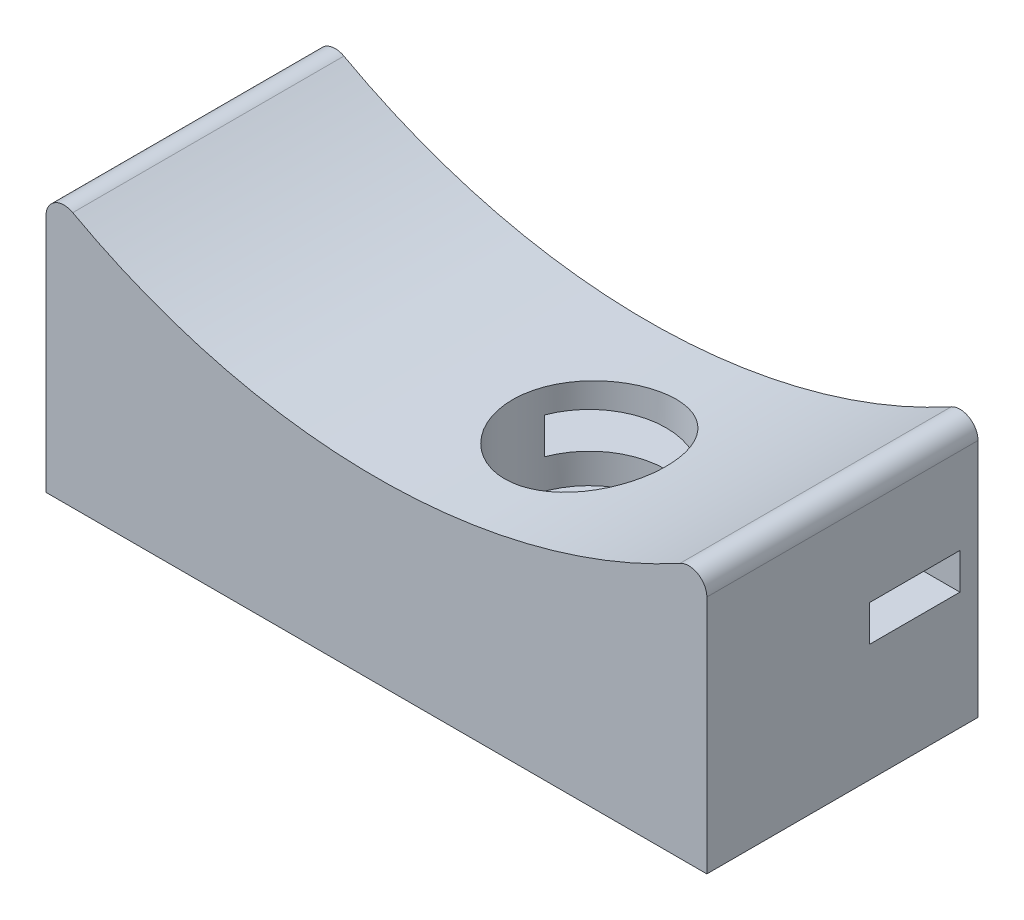
SolidWorks part; units mm, degrees
ref_plane "Front Plane" through (0, 0, 0) normal (0, 0, 1) x (1, 0, 0)
ref_plane "Top Plane" through (0, 0, 0) normal (0, 1, 0) x (1, 0, 0)
ref_plane "Right Plane" through (0, 0, 0) normal (1, 0, 0) x (0, 0, -1)
sketch "Sketch2" plane through (0, 0, 0) normal (0, 0, 1) x (1, 0, 0)
  line L0 (0, 15) -> (0, 0)
  line L1 (0, 0) -> (36.5591, 0)
  line L2 (36.5591, 0) -> (36.5591, 15)
  arc A0 (0, 15) -> (36.5591, 15) centre (18.2795, 44.8473) ccw
  dimension "D10" = 70
  dimension "D2" = 15
  dimension "D3" = 36.5591
extrude "Boss-Extrude2" add sketch "Sketch2" along normal blind 15
sketch "Sketch4" plane through (0, 0, 0) normal (0, -1, 0) x (1, 0, 0)
  line L0 (0, 15) -> (36.5591, 15) construction
  line L1 (36.5591, 15) -> (36.5591, 0) construction
  circle A0 centre (22.5591, 7.5) radius 2.5
  dimension "D3" = 5
  dimension "D1" = 7.5
  dimension "D2" = 14
extrude "Cut-Extrude1" cut sketch "Sketch4" against normal blind 15
ref_plane "Plane1" through (0, 9.8473, 0) normal (0, 1, 0) x (1, 0, 0)
sketch "Sketch5" plane through (0, 9.8473, 0) normal (0, 1, 0) x (1, 0, 0)
  circle A0 centre (22.5591, -7.5) radius 4.25
  dimension "D1" = 8.5
extrude "Cut-Extrude6" cut sketch "Sketch5" against normal mid plane 10
sketch "Sketch6" plane through (36.5591, 0, 0) normal (1, 0, 0) x (0, 0, -1)
  line L0 (0, 0) -> (0, 15) construction
  line L1 (-6, 8.5) -> (-1, 8.5)
  line L2 (-6, 8.5) -> (-6, 6.5)
  line L3 (-6, 6.5) -> (-1, 6.5)
  line L4 (-1, 8.5) -> (-1, 6.5)
  line L5 (-15, 0) -> (0, 0) construction
  dimension "D1" = 2
  dimension "D2" = 5
  dimension "D3" = 1
  dimension "D4" = 6.5
extrude "Cut-Extrude7" cut sketch "Sketch6" against normal through all
fillet "Fillet1" radius 1 2 edges at (0, 15, 7.5) (36.5591, 15, 7.5)
